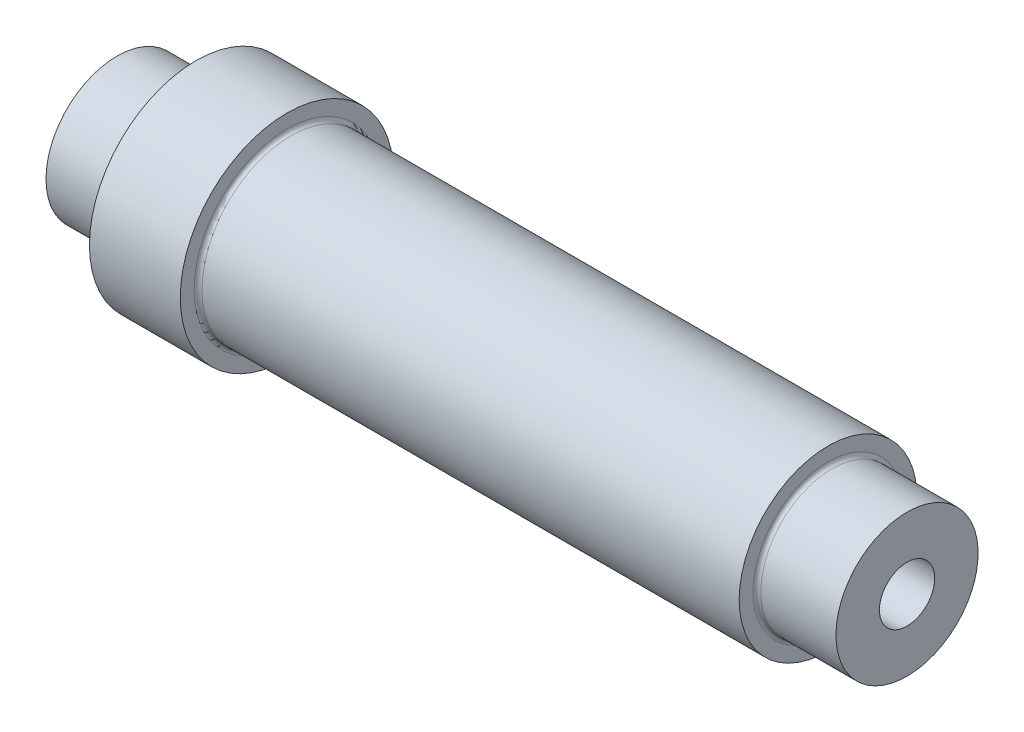
SolidWorks part; units mm, degrees
material "AISI 4340 Aço recozido"
ref_plane "Plano frontal" through (0, 0, 0) normal (0, 0, 1) x (1, 0, 0)
ref_plane "Plano superior" through (0, 0, 0) normal (0, 1, 0) x (1, 0, 0)
ref_plane "Plano direito" through (0, 0, 0) normal (1, 0, 0) x (0, 0, -1)
sketch "Esboço1" plane through (0, 0, 0) normal (0, 0, 1) x (1, 0, 0)
  line L0 (0, 0) -> (57.7383, 0) construction
  line L1 (0, 0) -> (0, 18)
  line L2 (0, 18) -> (20, 18)
  line L3 (20, 18) -> (20, 27)
  line L4 (20, 27) -> (43, 27)
  line L5 (43, 27) -> (43, 22.5)
  line L6 (43, 22.5) -> (180, 22.5)
  line L7 (180, 22.5) -> (180, 18)
  line L8 (180, 18) -> (200, 18)
  line L9 (200, 18) -> (200, 0)
  line L10 (0, 0) -> (200, 0)
  dimension "D1" = 45
  dimension "D2" = 160
  dimension "D3" = 36
  dimension "D4" = 20
  dimension "D5" = 54
  dimension "D6" = 23
revolve "Revolução1" add sketch "Esboço1" angle 360 about L0
hole_wizard "Broca de rosquear para tarraxa de M161" positions "3DSketch1" profile "Esboço2" hole size "M16" standard "ISO"
sketch3d "3DSketch1"
  point P0 (200, 0, 0)
  point P20 (0, 0, 0)
  point P23 (0, 0, 0)
sketch "Esboço2" plane through (200, 0, 0) normal (0, 1, 0) x (0, 0, -1)
  line L0 (0, 0) -> (0, 34.206)
  line L1 (0, 34.206) -> (7, 30)
  line L2 (7, 30) -> (7, 0)
  line L5 (7, 0) -> (0, 0)
  line L10 (0, 34.206) -> (-7, 30) construction
  line L11 (0, -6.35) -> (0, 107.95) construction
  dimension "Hole Dia." = 14
  dimension "Hole Depth" = 30
  dimension "Drill Angle" = 118
fillet "Filete1" radius 1 3 edges at (20, 0, 18) (180, 0, 18) (43, 0, 22.5)
equation "\"escala\"= 1                        'projeto - escala geral"
equation "\"escala_disco-arma\"= 3                                                                  'disco arma - escala geometria disco arma"
equation "\"arma_eixo-furo_folga\"= 4                                                              'disco arma - folga entre furo arma e eixo"
equation "\"arma_rebaixo-camisa_raio\"= 12                                                         'disco arma - raio do rebaixo da camisa da arma "
equation "\"arma_rebaixo-camisa_b\"= \"rolamento_b-esp\" + (\"arma-espessura\"-\"rolamento_b-esp\")/2     'disco arma - profundidade rebaixo camisa"
equation "\"arma-espessura\"= 50                                                                    'disco arma - espessura disco arma"
equation "\"rolamento_D-ext\"= 85               'rolamento arma - diametro externo"
equation "\"rolamento_D1-ext\"= 75             'rolamento arma - ressalto diam externo"
equation "\"rolamento_d-int\"= 45               'rolamento arma - diametro interno"
equation "\"rolamento_b-esp\"= 23               'rolamento arma - espessura"
equation "\"camisa_largura\"=115                                                        'camisa arma - tamanho do lado"
equation "\"camisa_raio\"= 16                                                           'camisa arma - raio canto interno"
equation "\"camisa_raio-alivio\"= 6                                                    'camisa arma - raio de alivio de tensoes no encaixe da arma"
equation "\"camisa_rebaixo_rolamento\"= 1 * \"rolamento_b-esp\""
equation "\"camisa_comprimento-centro\"= 2*(\"arma_rebaixo-camisa_b\")+\"polia_espessura\" "
equation "\"camisa_furos_dist\"= 83"
equation "\"camisa_furos_prof\"= 30"
equation "\"polia_espessura\"= 40  "
equation "\"polia_diam_eff\"= 142"
equation "\"eixo-arm_diam\"= \"rolamento_d-int\"                                                                'eixo arma - diametro"
equation "\"D1@Esboço1\"=\"eixo-arm_diam\""
equation "\"D2@Esboço1\"=\"eixo-arm_comp-entre-mancais\""
equation "\"eixo-arm_comp-espacador\"= \"eixo-arm_folga_mancal-arma\" + \"arma-espessura\"-\"arma_rebaixo-camisa_b\" - \"eixo-arm_allowable-movement\"/2"
equation "\"mancal-arm_rebaixo-eixo_profundidade\"= 20"
equation "\"D3@Esboço1\"=\"mancal-arm_rebaixo-eixo_diametro\""
equation "\"D4@Esboço1\"=\"mancal-arm_rebaixo-eixo_profundidade\""
equation "\"D5@Esboço1\" = \"rolamento_d2-int\""
equation "\"D6@Esboço1\"=\"eixo-arm_comp-espacador\""
equation "\"eixo-arm_prof-furo-fix\"= 30"
equation "\"rolamento_d2-int\"= 54             'rolamento arma - ressalto diam interno"
equation "\"mancal-arm_rebaixo-eixo_diametro\"= 2 * \"eixo-arm_diam\" - \"rolamento_d2-int\""
equation "\"eixo-arm_folga_mancal-arma\"= 10"
equation "\"eixo-arm_allowable-movement\"= 1"
equation "\"eixo-arm_comp-entre-mancais\"= 2*\"eixo-arm_folga_mancal-arma\" + 2*\"arma-espessura\" + \"polia_espessura\"    'eixo arma - comprimento entre mancais"
